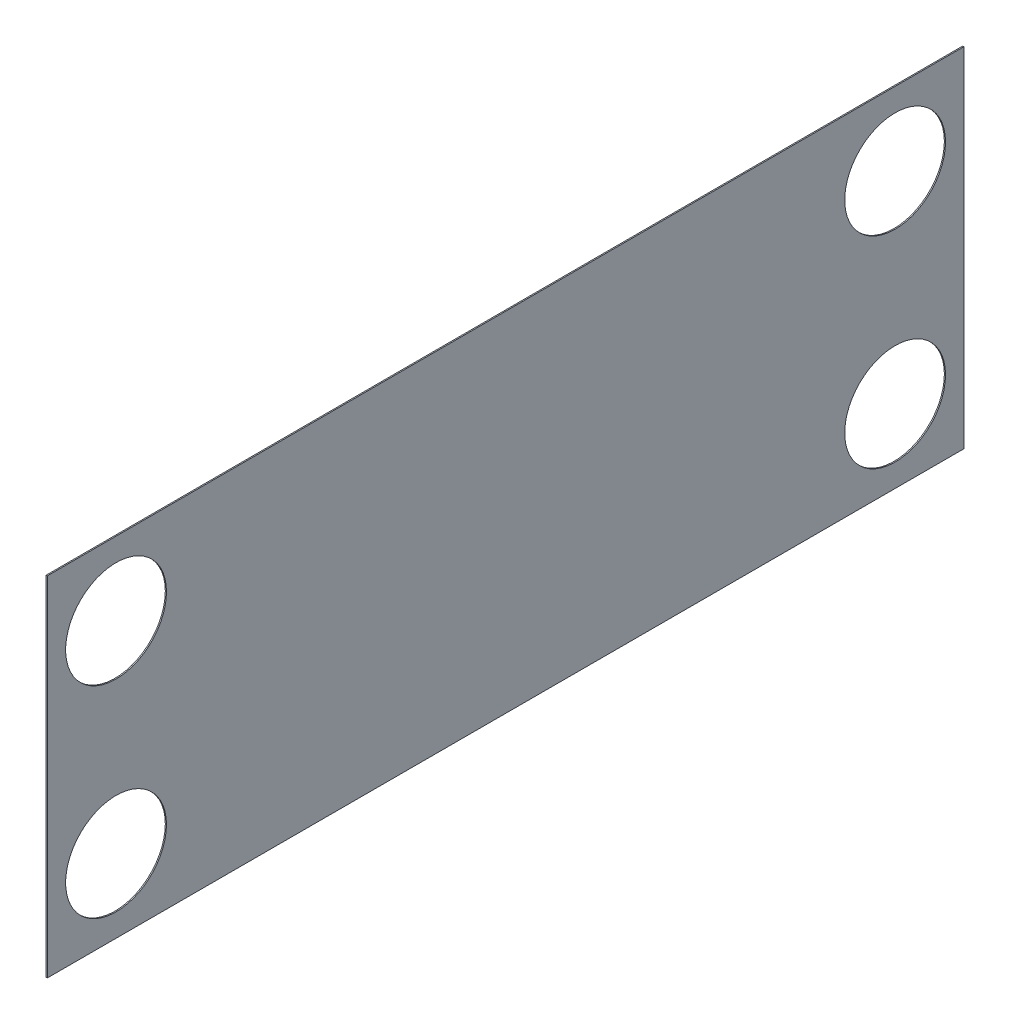
SolidWorks part; units mm, degrees
material "Low Carbon Steel"
ref_plane "Front Plane" through (0, 0, 0) normal (0, 0, 1) x (1, 0, 0)
ref_plane "Top Plane" through (0, 0, 0) normal (0, 1, 0) x (1, 0, 0)
ref_plane "Right Plane" through (0, 0, 0) normal (1, 0, 0) x (0, 0, -1)
sketch "Sketch1" plane through (0, 0, 0) normal (1, 0, 0) x (0, 0, -1)
  line L0 (50, 19) -> (-50, -19) construction
  line L1 (-50, 19) -> (50, 19)
  line L2 (-50, 19) -> (-50, -19)
  line L3 (-50, -19) -> (50, -19)
  line L4 (50, 19) -> (50, -19)
  dimension "D1" = 100
  dimension "D2" = 38
extrude "Boss-Extrude1" add sketch "Sketch1" along normal blind 0.127
hole_wizard "M10 Clearance Hole1" positions "Sketch2" profile "Sketch3" hole size "M10" standard "Peddi DIN" end condition through all
sketch "Sketch2" plane through (0.127, 0, 0) normal (1, 0, 0) x (0, 0, -1)
  line L0 (42.5, 11) -> (42.5, -11) construction
  line L1 (42.5, -11) -> (-42.5, 11) construction
  line L2 (-42.5, 11) -> (-42.5, -11) construction
  line L3 (-42.5, -11) -> (42.5, -11) construction
  point P0 (-42.5, 11)
  point P2 (-42.5, -11)
  point P4 (42.5, 11)
  point P6 (42.5, -11)
  dimension "D1" = 22
  dimension "D2" = 85
sketch "Sketch3" plane through (0.127, 11, 42.5) normal (0, 1, 0) x (0, 0, -1)
  line L0 (0, 0) -> (0, 0.127)
  line L1 (0, 0.127) -> (5.5, 0.127)
  line L2 (5.5, 0.127) -> (5.5, 0)
  line L5 (5.5, 0) -> (0, 0)
  line L11 (0, -6.35) -> (0, 107.95) construction
  dimension "Thru Hole Dia." = 11
  dimension "Thru Hole Depth" = 0.127
other "Freeze***"
